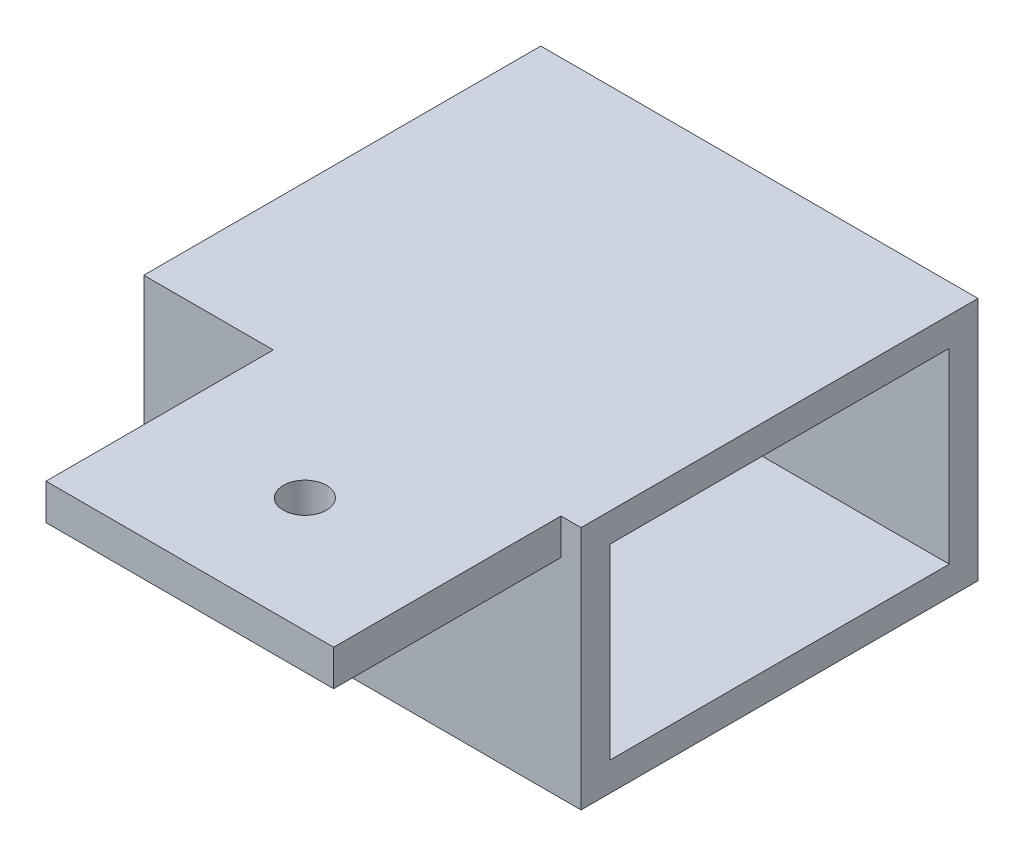
SolidWorks part; units mm, degrees
ref_plane "Front Plane" through (0, 0, 0) normal (0, 0, 1) x (1, 0, 0)
ref_plane "Top Plane" through (0, 0, 0) normal (0, 1, 0) x (1, 0, 0)
ref_plane "Right Plane" through (0, 0, 0) normal (1, 0, 0) x (0, 0, -1)
ref_plane "PZ_m34_000" through (0, 0, -34) normal (0, 0, 1) x (1, 0, 0)
sketch "S_box1" plane through (0, 0, -34) normal (0, 0, 1) x (1, 0, 0)
  line L0 (-10, -4) -> (10, -4)
  line L1 (10, -4) -> (10, -1.5)
  line L2 (10, -1.5) -> (-10, -1.5)
  line L3 (-10, -1.5) -> (-10, -4)
  dimension "P1" = 10
  dimension "P2" = 4
  dimension "P3" = 10
  dimension "P4" = 4
  dimension "P5" = 10
  dimension "P6" = 1.5
  dimension "P7" = 10
  dimension "P8" = 1.5
extrude "Boss_1" add sketch "S_box1" along normal blind 42
ref_plane "PZ_m35_400" through (0, 0, -35.4) normal (0, 0, 1) x (1, 0, 0)
sketch "S_box2" plane through (0, 0, -35.4) normal (0, 0, 1) x (1, 0, 0)
  line L0 (-19, -18.5) -> (11.4, -18.5)
  line L1 (11.4, -18.5) -> (11.4, -1.5)
  line L2 (11.4, -1.5) -> (-19, -1.5)
  line L3 (-19, -1.5) -> (-19, -18.5)
  dimension "P1" = 19
  dimension "P2" = 18.5
  dimension "P3" = 11.4
  dimension "P4" = 18.5
  dimension "P5" = 11.4
  dimension "P6" = 1.5
  dimension "P7" = 19
  dimension "P8" = 1.5
extrude "Boss_2" add sketch "S_box2" along normal blind 27.6
ref_plane "PZ_m33_400" through (0, 0, -33.4) normal (0, 0, 1) x (1, 0, 0)
sketch "S_cut3" plane through (0, 0, -33.4) normal (0, 0, 1) x (1, 0, 0)
  line L0 (-19.1, -16.5) -> (11.5, -16.5)
  line L1 (11.5, -16.5) -> (11.5, -3.5)
  line L2 (11.5, -3.5) -> (-19.1, -3.5)
  line L3 (-19.1, -3.5) -> (-19.1, -16.5)
  dimension "P1" = 19.1
  dimension "P2" = 16.5
  dimension "P3" = 11.5
  dimension "P4" = 16.5
  dimension "P5" = 11.5
  dimension "P6" = 3.5
  dimension "P7" = 19.1
  dimension "P8" = 3.5
extrude "Pocket_3" cut sketch "S_cut3" along normal blind 23.6
ref_plane "PY_m4_100" through (0, -4.1, 0) normal (0, 1, 0) x (1, 0, 0)
sketch "S_hole4" plane through (0, -4.1, 0) normal (0, 1, 0) x (1, 0, 0)
  circle A0 centre (0, 0) radius 1.5
  dimension "D1_S_hole4" = 3
extrude "Hole_4" cut sketch "S_hole4" along normal blind 2.7
equation "\"plate_t\" = 3"
equation "\"clearance\" = 0.4"
